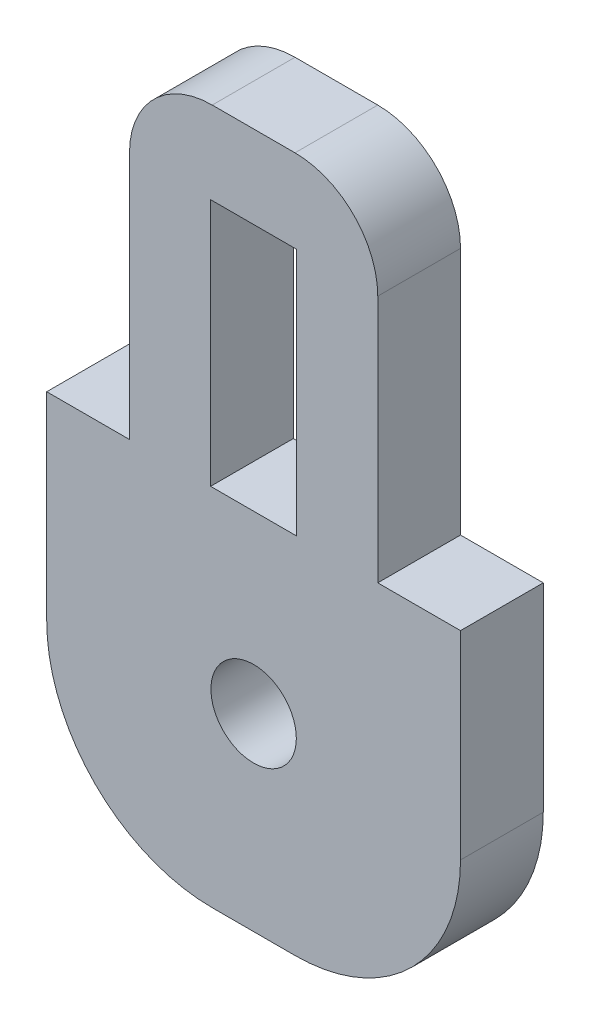
SolidWorks part; units mm, degrees
ref_plane "Front" through (0, 0, 0) normal (0, 0, 1) x (1, 0, 0)
ref_plane "Top" through (0, 0, 0) normal (0, 1, 0) x (1, 0, 0)
ref_plane "Right" through (0, 0, 0) normal (1, 0, 0) x (0, 0, -1)
sketch "Sketch1" plane through (0, 0, 0) normal (0, 0, 1) x (1, 0, 0)
  line L0 (0, 19.685) -> (0, 0) construction
  line L1 (-1.5875, 19.685) -> (1.5875, 19.685)
  line L2 (-7.9375, 6.985) -> (-7.9375, -0.635)
  line L3 (-1.5875, -6.985) -> (1.5875, -6.985)
  line L4 (7.9375, 6.985) -> (7.9375, -0.635)
  line L5 (-7.9375, 6.985) -> (7.9375, -6.985) construction
  line L6 (-7.9375, -6.985) -> (7.9375, 6.985) construction
  line L7 (-7.9375, 6.985) -> (-4.7625, 6.985)
  line L8 (-4.7625, 6.985) -> (-4.7625, 16.51)
  line L9 (7.9375, 6.985) -> (4.7625, 6.985)
  line L10 (4.7625, 6.985) -> (4.7625, 16.51)
  line L12 (-1.651, 6.985) -> (1.651, 6.985)
  line L13 (-1.651, 6.985) -> (-1.651, 16.51)
  line L14 (-1.651, 16.51) -> (1.651, 16.51)
  line L15 (1.651, 6.985) -> (1.651, 16.51)
  line L16 (-1.651, 6.985) -> (1.651, 16.51) construction
  line L17 (-1.651, 16.51) -> (1.651, 6.985) construction
  arc A0 (1.5875, -6.985) -> (7.9375, -0.635) centre (1.5875, -0.635) ccw
  arc A1 (-7.9375, -0.635) -> (-1.5875, -6.985) centre (-1.5875, -0.635) ccw
  arc A2 (1.5875, 19.685) -> (4.7625, 16.51) centre (1.5875, 16.51) cw
  arc A3 (-4.7625, 16.51) -> (-1.5875, 19.685) centre (-1.5875, 16.51) cw
  circle A4 centre (0, 0.254) radius 1.6383
  point P0 (0, 0)
  point P5 (0, 11.7475)
  point P27 (4.7625, 19.685)
  point P30 (-4.7625, 19.685)
  dimension "D7" = 3.175
  dimension "D8" = 3.2766
  dimension "D10" = 6.35
  dimension "D1" = 13.97
  dimension "D2" = 9.525
  dimension "D3" = 15.875
  dimension "D4" = 12.7
  dimension "D5" = 3.175
  dimension "D6" = 3.302
  dimension "D9" = 6.731
extrude "Boss-Extrude1" add sketch "Sketch1" along normal blind 3.175
